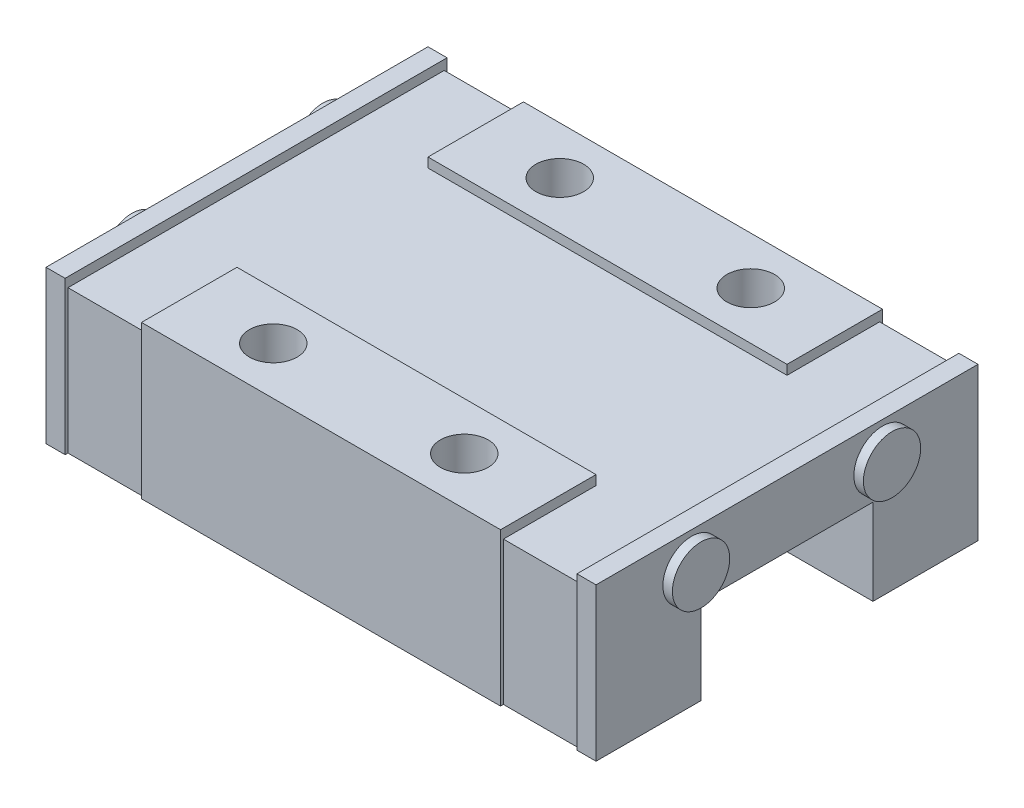
SolidWorks part; units mm, degrees
ref_plane "Front Plane" through (0, 0, 0) normal (0, 0, 1) x (1, 0, 0)
ref_plane "Top Plane" through (0, 0, 0) normal (0, 1, 0) x (1, 0, 0)
ref_plane "Right Plane" through (0, 0, 0) normal (1, 0, 0) x (0, 0, -1)
sketch "Sketch1" plane through (0, 0, 0) normal (0, 1, 0) x (1, 0, 0)
  line L1 (0, 0) -> (18.8, 0)
  line L2 (0, 0) -> (0, 20)
  line L3 (0, 20) -> (18.8, 20)
  line L4 (18.8, 0) -> (18.8, 20)
  dimension "D1" = 18.8
  dimension "D2" = 20
extrude "Boss-Extrude1" add sketch "Sketch1" along normal blind 8
sketch "Sketch2" plane through (0, 8, 0) normal (0, 1, 0) x (1, 0, 0)
  line L0 (0, 20) -> (0, 0) construction
  line L1 (0, 0) -> (18.8, 0) construction
  circle A0 centre (4.4, 2.5) radius 1.25
  circle A1 centre (14.4, 2.5) radius 1.25
  circle A2 centre (14.4, 17.5) radius 1.25
  circle A3 centre (4.4, 17.5) radius 1.25
  point P14 (6.8168, 10.221)
  dimension "D1" = 4.4
  dimension "D5" = 10
  dimension "D2" = 2.5
  dimension "D6" = 15
  dimension "D3" = 2
  dimension "D4" = 2
extrude "Cut-Extrude1" cut sketch "Sketch2" against normal blind 7
sketch "Sketch3" plane through (0, 8, 0) normal (0, 1, 0) x (1, 0, 0)
  line L0 (0, 20) -> (0, 0) construction
  line L1 (0, 15) -> (18.8, 15)
  line L2 (0, 15) -> (0, 5)
  line L3 (0, 5) -> (18.8, 5)
  line L4 (18.8, 15) -> (18.8, 5)
  line L5 (18.8, 0) -> (18.8, 20) construction
  line L6 (0, 0) -> (18.8, 0) construction
  dimension "D1" = 10
  dimension "D2" = 5
extrude "Cut-Extrude2" cut sketch "Sketch3" against normal blind 0.5
sketch "Sketch4" plane through (18.8, 0, 0) normal (1, 0, 0) x (0, 0, -1)
  line L0 (0, 0) -> (20, 0) construction
  line L1 (5.5, 4.5) -> (14.5, 4.5)
  line L2 (5.5, 4.5) -> (5.5, 0)
  line L3 (5.5, 0) -> (14.5, 0)
  line L4 (14.5, 4.5) -> (14.5, 0)
  line L5 (0, 8) -> (0, 0) construction
  dimension "D1" = 9
  dimension "D2" = 4.5
  dimension "D3" = 5.5
extrude "Cut-Extrude3" cut sketch "Sketch4" against normal blind 20 contours L2 L1 L4 L3
sketch "Sketch5" plane through (18.8, 0, 0) normal (1, 0, 0) x (0, 0, -1)
  line L0 (0, 8) -> (0, 0) construction
  line L1 (5.5, 0) -> (0.15, 0)
  line L2 (5.5, 0) -> (5.5, 4.5)
  line L3 (5.5, 7.5) -> (0.15, 7.5)
  line L4 (0.15, 0) -> (0.15, 7.5)
  line L5 (14.5, 0) -> (19.85, 0)
  line L6 (14.5, 0) -> (14.5, 4.5)
  line L7 (14.5, 7.5) -> (19.85, 7.5)
  line L8 (19.85, 0) -> (19.85, 7.5)
  line L9 (5.5, 7.5) -> (14.5, 7.5)
  line L11 (5.5, 4.5) -> (14.5, 4.5)
  line L13 (20, 8) -> (20, 0) construction
  dimension "D1" = 7.5
  dimension "D2" = 0.15
  dimension "D3" = 0.15
extrude "Boss-Extrude2" add sketch "Sketch5" along normal blind 4
pattern_linear "LPattern1" count 2 spacing 22.8 along (-1, 0, 0) of "Boss-Extrude2"
sketch "Sketch6" plane through (22.8, 0, 0) normal (1, 0, 0) x (0, 0, -1)
  line L0 (15, 7.5) -> (15, 8) construction
  line L1 (0, 0) -> (5, 0)
  line L2 (0, 0) -> (0, 8)
  line L3 (0, 8) -> (5, 8)
  line L5 (20, 0) -> (15, 0)
  line L6 (20, 0) -> (20, 8)
  line L7 (20, 8) -> (15, 8)
  line L12 (5.5, 4.5) -> (14.5, 4.5)
  line L14 (5.5, 0) -> (5, 0)
  line L15 (5.5, 0) -> (5.5, 4.5)
  line L18 (14.5, 0) -> (15, 0)
  line L19 (14.5, 0) -> (14.5, 4.5)
  line L23 (5, 8) -> (15, 8)
extrude "Boss-Extrude3" add sketch "Sketch6" along normal blind 1
pattern_linear "LPattern3" count 2 spacing 27.8 along (-1, 0, 0) of "Boss-Extrude3"
sketch "Sketch8" plane through (23.8, 0, 0) normal (1, 0, 0) x (0, 0, -1)
  line L0 (5.5, 0) -> (5.5, 4.5) construction
  line L1 (14.5, 4.5) -> (14.5, 0) construction
  line L2 (20, 8) -> (0, 8) construction
  circle A0 centre (5, 6.2) radius 1.5
  circle A1 centre (15, 6.2) radius 1.5
  dimension "D1" = 0.5
  dimension "D2" = 0.5
  dimension "D3" = 1.8
  dimension "D4" = 1.8
extrude "Boss-Extrude4" add sketch "Sketch8" along normal blind 0.5
pattern_linear "LPattern4" count 2 spacing 29.3 along (-1, 0, 0) of "Boss-Extrude4"
sketch "Sketch9" plane through (0, 7.5, 0) normal (0, 1, 0) x (1, 0, 0)
